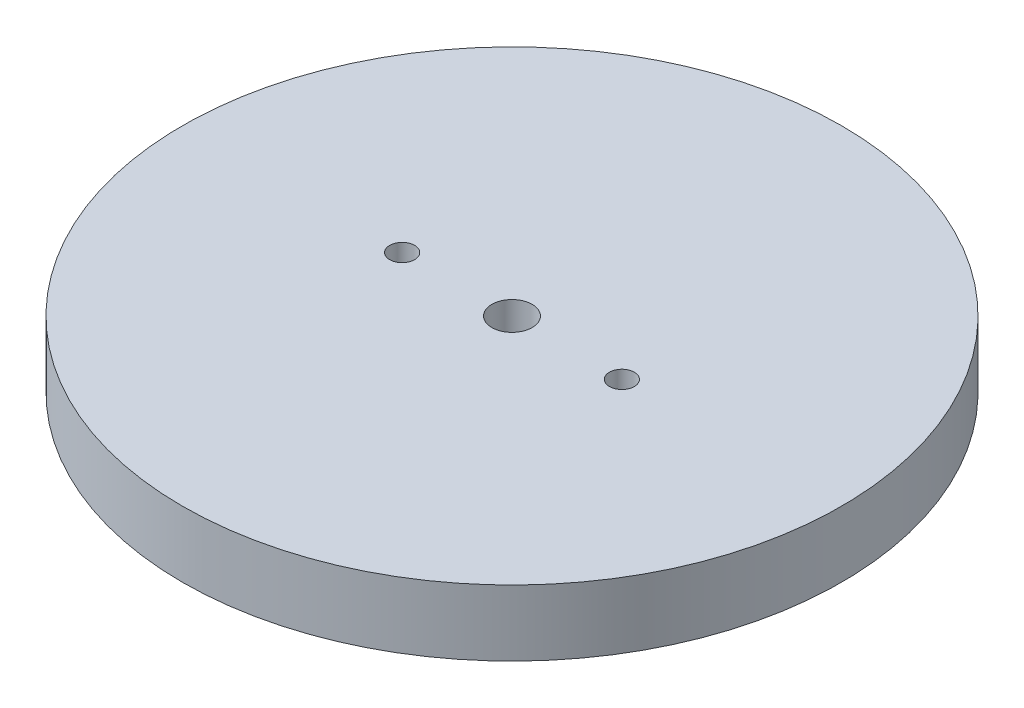
SolidWorks part; units mm, degrees
ref_plane "Front Plane" through (0, 0, 0) normal (0, 0, 1) x (1, 0, 0)
ref_plane "Top Plane" through (0, 0, 0) normal (0, 1, 0) x (1, 0, 0)
ref_plane "Right Plane" through (0, 0, 0) normal (1, 0, 0) x (0, 0, -1)
sketch "Sketch1" plane through (0, 0, 0) normal (0, 1, 0) x (1, 0, 0)
  circle A2 centre (-24.4835, -19.1453) radius 45
  circle A3 centre (-24.4835, -19.1453) radius 2.75
  circle A4 centre (-39.4835, -19.1453) radius 1.7
  circle A5 centre (-9.4835, -19.1453) radius 1.7
  point P7 (-6.2129, 0)
  point P8 (-30.8455, 0)
  point P9 (-6.9017, 0)
  point P10 (-13.5344, -19.1453)
  point P11 (-39.4835, -19.1453)
  point P12 (11.1254, -19.1453)
  point P13 (0, 0)
  dimension "D2" = 3.4
  dimension "D3" = 90
  dimension "D1" = 5.5
  dimension "D4" = 15
  dimension "D5" = 15
extrude "Boss-Extrude1" add sketch "Sketch1" along normal blind 9
